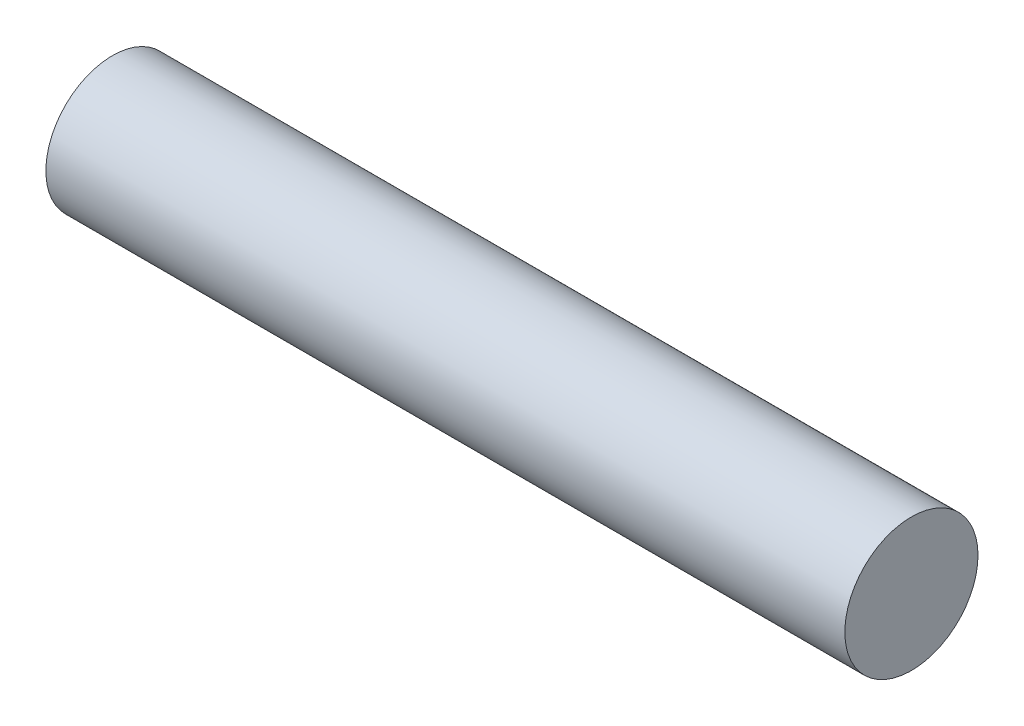
SolidWorks part; units mm, degrees
material "ABS"
ref_plane "Front Plane" through (0, 0, 0) normal (0, 0, 1) x (1, 0, 0)
ref_plane "Top Plane" through (0, 0, 0) normal (0, 1, 0) x (1, 0, 0)
ref_plane "Right Plane" through (0, 0, 0) normal (1, 0, 0) x (0, 0, -1)
sketch "Sketch2" plane through (0, 0, 0) normal (1, 0, 0) x (0, 0, -1)
  circle A0 centre (-4536.8775, 2613.6602) radius 18.75
  dimension "D1" = 37.5
extrude "Boss-Extrude1" add sketch "Sketch2" along normal blind 225
